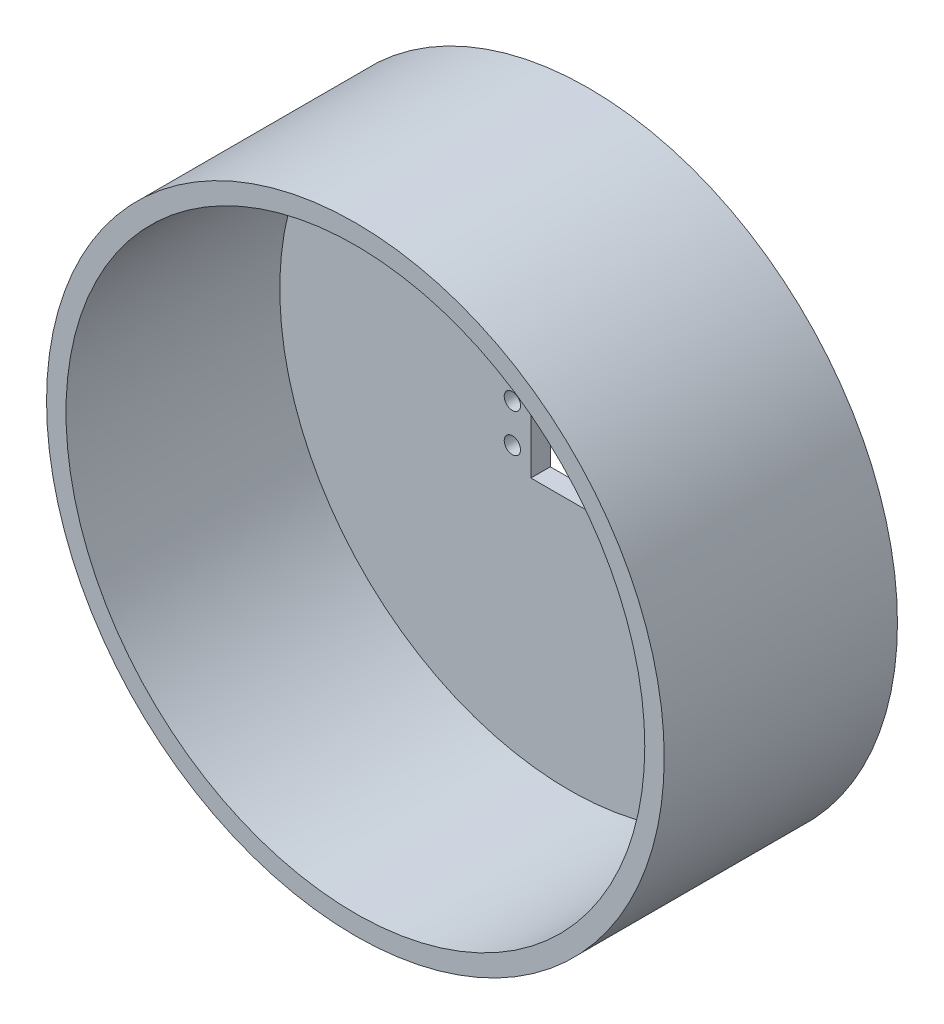
SolidWorks part; units mm, degrees
ref_plane "Front Plane" through (0, 0, 0) normal (0, 0, 1) x (1, 0, 0)
ref_plane "Top Plane" through (0, 0, 0) normal (0, 1, 0) x (1, 0, 0)
ref_plane "Right Plane" through (0, 0, 0) normal (1, 0, 0) x (0, 0, -1)
sketch "Sketch1" plane through (0, 0, 0) normal (0, 0, 1) x (1, 0, 0)
  circle A0 centre (0, 0) radius 79.45
  dimension "D1" = 158.9
extrude "Boss-Extrude1" add sketch "Sketch1" along normal blind 60
shell "Shell1" thickness 5
sketch "Sketch2" plane through (0, 0, 5) normal (0, 0, 1) x (1, 0, 0)
  circle A0 centre (0, 0) radius 2.5
extrude "Cut-Extrude1" cut sketch "Sketch2" against normal blind 60
sketch "Sketch3" plane through (0, 0, 0) normal (0, 0, -1) x (-1, 0, 0)
  line L0 (-30.0485, 9.8546) -> (9.8515, 9.8485)
  line L1 (-29.7485, 9.8545) -> (-36.0985, 9.8555) construction
  line L2 (15.9015, 9.8476) -> (9.5515, 9.8485) construction
  line L3 (9.8515, 9.8485) -> (9.8515, -9.8515)
  line L4 (9.5485, -9.8515) -> (15.8985, -9.8524) construction
  line L5 (9.8515, -9.8515) -> (-30.0515, -9.8454)
  line L6 (-36.1015, -9.8445) -> (-29.7515, -9.8455) construction
  line L7 (-30.0515, -9.8454) -> (-30.0485, 9.8546)
  circle A0 centre (-34.8104, 4.9303) radius 2.1
  circle A1 centre (-34.8119, -4.9197) radius 2.1
  circle A2 centre (14.6104, -4.9272) radius 2.1
  circle A3 centre (14.6119, 4.9228) radius 2.1
  dimension "D1" = 39.9
extrude "Cut-Extrude2" cut sketch "Sketch3" against normal blind 60
